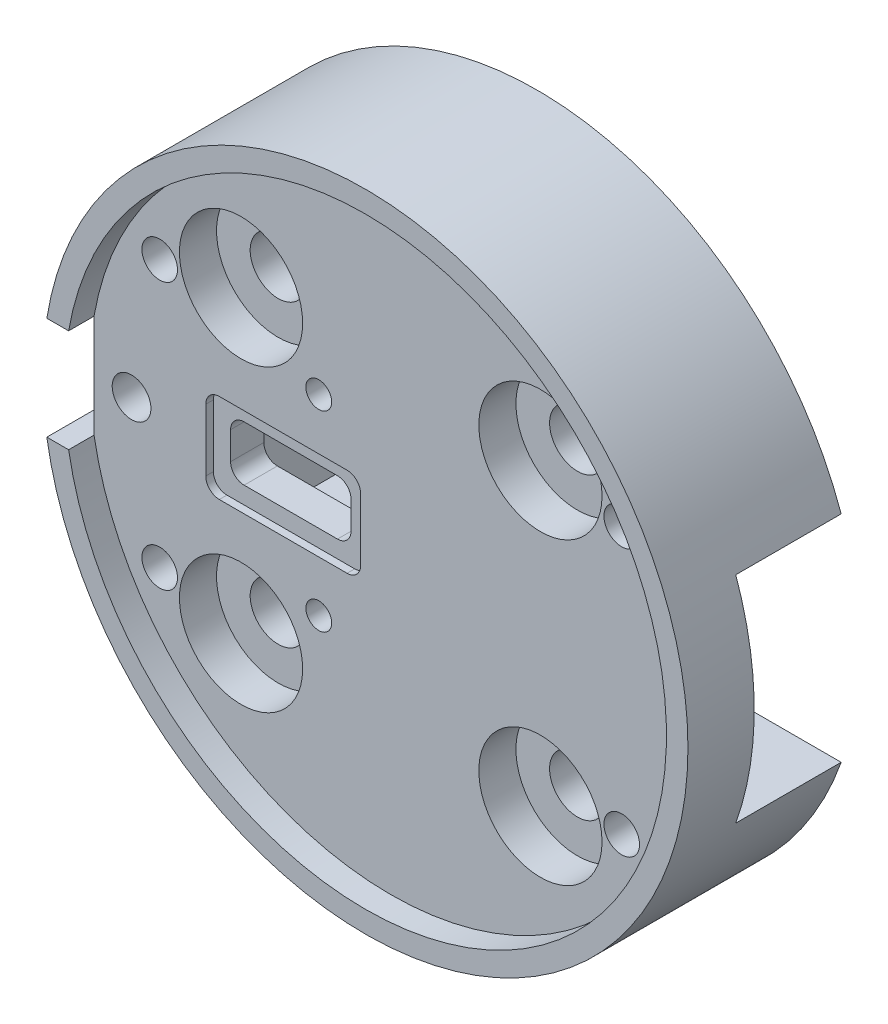
SolidWorks part; units mm, degrees
ref_plane "Front Plane" through (0, 0, 0) normal (0, 0, 1) x (1, 0, 0)
ref_plane "Top Plane" through (0, 0, 0) normal (0, 1, 0) x (1, 0, 0)
ref_plane "Right Plane" through (0, 0, 0) normal (1, 0, 0) x (0, 0, -1)
sketch "Sketch1" plane through (0, 0, 0) normal (0, 0, 1) x (1, 0, 0)
  circle A0 centre (0, 0) radius 38.1
  dimension "D1" = 76.2
extrude "Boss-Extrude1" add sketch "Sketch1" along normal blind 17.272 contours A0
sketch "Sketch2" plane through (0, 0, 17.272) normal (0, 0, 1) x (1, 0, 0)
  line L0 (0, 0) -> (38.1, 0) construction
  line L2 (0, 0) -> (17.6777, 17.6777) construction
  circle A0 centre (17.6777, 17.6777) radius 2.9
  circle A2 centre (17.6777, -17.6777) radius 2.9
  circle A3 centre (-17.6777, -17.6777) radius 2.9
  circle A5 centre (0, 0) radius 38.1 construction
  circle A6 centre (-17.6777, 17.6777) radius 2.9 [skipped]
  circle A7 centre (-17.6777, 17.6777) radius 2.9
  point P0 (17.6777, 17.6777)
  point P8 (17.6777, -17.6777)
  point P11 (-17.6777, -17.6777)
  point P39 (-17.6777, 17.6777)
  dimension "D1" = 5.8
  dimension "D4" = 5.8
  dimension "D3" = 45
  dimension "D5" = 25
  dimension "D6" = 25
  dimension "D2" = 4
hole_wizard "CBORE for M6 Hex Head Bolt1" positions "Sketch2" profile "Sketch5" counterbore size "M6" standard "ANSI Metric" end condition through all
sketch "Sketch5" plane through (17.6777, 17.6777, 17.272) normal (1, 0, 0) x (0, -1, 0)
  line L0 (0, 0) -> (0, 17.272)
  line L1 (0, 17.272) -> (3.3, 17.272)
  line L3 (3.3, 17.272) -> (3.3, 4.38)
  line L4 (3.3, 4.38) -> (7.275, 4.38)
  line L5 (7.275, 4.38) -> (7.275, 0)
  line L7 (7.275, 0) -> (0, 0)
  line L11 (0, -6.35) -> (0, 107.95) construction
  dimension "Thru Hole Dia." = 6.6
  dimension "Thru Hole Depth" = 17.272
  dimension "C'Bore Dia." = 14.55
  dimension "C'Bore Depth" = 4.38
sketch "Sketch6" plane through (0, 0, 17.272) normal (0, 0, 1) x (1, 0, 0)
  circle A1 centre (-5.653, 24.6769) radius 1.515
  dimension "D1" = 3.03
extrude "Pin_for_M6" cut sketch "Sketch6" against normal blind 17.272
sketch "Sketch7" plane through (0, 0, 17.272) normal (0, 0, 1) x (1, 0, 0)
  line L0 (0, 0) -> (0, 38.1) construction
  line L10 (0, 0) -> (27.2798, 15.75) construction
  line L12 (0, 0) -> (27.2798, -15.75) construction
  line L14 (-27.2798, 15.75) -> (0, 0) construction
  line L15 (0, 0) -> (-27.2798, -15.75) construction
  circle A0 centre (27.2798, 15.75) radius 2.4
  circle A1 centre (0, 0) radius 31.5 construction
  circle A2 centre (0, 0) radius 38.1 construction
  circle A4 centre (-27.2798, 15.75) radius 2.4
  circle A5 centre (27.2798, -15.75) radius 2.4
  circle A6 centre (-27.2798, -15.75) radius 2.4
  point P0 (27.2798, 15.75)
  point P5 (-27.2798, 15.75)
  point P17 (27.2798, -15.75)
  point P19 (-27.2798, -15.75)
  point P21 (-27.2798, 15.75)
  point P34 (-27.2798, -15.75)
  point P36 (27.2798, -15.75)
  point P38 (27.2798, 15.75)
  dimension "D2" = 4.8
  dimension "D1" = 4.8
  dimension "D3" = 63
  dimension "D4" = 60
  dimension "D5" = 60
  dimension "D6" = 120
hole_wizard "M5x0.8 Tapped Hole1" positions "Sketch7" profile "Sketch9" tap size "M5x0.8" standard "ANSI Metric" end condition through all
sketch "Sketch9" plane through (27.2798, 15.75, 17.272) normal (1, 0, 0) x (0, -1, 0)
  line L0 (0, 0) -> (0, 17.272)
  line L1 (0, 17.272) -> (2.1, 17.272)
  line L2 (2.1, 17.272) -> (2.1, 0)
  line L5 (2.1, 0) -> (0, 0)
  line L11 (0, -6.35) -> (0, 107.95) construction
  dimension "Thru Tap Drill Dia." = 4.2
  dimension "Thru Tap Drill Depth" = 17.272
cosmetic thread "Hole Thread1" parameters "D2"=5
cosmetic thread "Hole Thread2" parameters "D2"=5
cosmetic thread "Hole Thread3" parameters "D2"=5
cosmetic thread "Hole Thread4" parameters "D2"=5
cosmetic thread "Hole Thread5" parameters "D2"=5
cosmetic thread "Hole Thread6" parameters "D2"=5
cosmetic thread "Hole Thread7" parameters "D2"=5
cosmetic thread "Hole Thread8" parameters "D2"=5
sketch "Sketch10" plane through (0, 0, 17.272) normal (0, 0, 1) x (1, 0, 0)
  line L1 (-18.212, 3.2385) -> (-7.188, 3.2385)
  line L2 (-19.812, 1.6385) -> (-19.812, -1.6385)
  line L3 (-18.212, -3.2385) -> (-7.188, -3.2385)
  line L4 (-5.588, 1.6385) -> (-5.588, -1.6385)
  circle A0 centre (-5.653, 24.6769) radius 1.05
  arc A1 (-5.588, 1.6385) -> (-7.188, 3.2385) centre (-7.188, 1.6385) ccw
  arc A2 (-7.188, -3.2385) -> (-5.588, -1.6385) centre (-7.188, -1.6385) ccw
  arc A3 (-18.212, -3.2385) -> (-19.812, -1.6385) centre (-18.212, -1.6385) cw
  arc A4 (-19.812, 1.6385) -> (-18.212, 3.2385) centre (-18.212, 1.6385) cw
  point P4 (-19.812, 0)
  point P6 (-5.588, 0)
  point P13 (-5.588, 3.2385)
  point P18 (-19.812, -3.2385)
  point P21 (-19.812, 3.2385)
  dimension "D3" = 2.1
  dimension "D5" = 1.6
  dimension "D1" = 14.224
  dimension "D2" = 6.477
  dimension "D4" = 5.588
extrude "Spring_Pin_Hole" cut sketch "Sketch10" against normal blind 17.272
sketch "Sketch13" plane through (0, 0, 17.272) normal (0, 0, 1) x (1, 0, 0)
  line L2 (-37.6121, 6.078) -> (-35.0367, 6.078)
  line L4 (-37.6121, -6.078) -> (-35.0367, -6.078)
  arc A1 (-35.0367, 6.078) -> (35.0873, 5.7787) centre (0, 0) cw
  arc A3 (-35.0367, -6.078) -> (35.0873, 5.7787) centre (0, 0) ccw
  circle A5 centre (0, 0) radius 38.1 construction
  arc A7 (-37.6121, -6.078) -> (37.6592, -5.7785) centre (0, 0) ccw
  arc A16 (-37.6121, 6.078) -> (37.6592, -5.7785) centre (0, 0) cw
  dimension "D1" = 35.56
extrude "Allignment_Border" add sketch "Sketch13" along normal blind 3
sketch "Sketch15" plane through (0, 0, 17.272) normal (0, 0, 1) x (1, 0, 0)
  line L0 (-7.188, 3.2385) -> (-18.212, 3.2385) construction
  line L1 (-20.244, 5.2705) -> (-5.156, 5.2705)
  line L2 (-21.844, 3.6705) -> (-21.844, -3.6705)
  line L3 (-20.244, -5.2705) -> (-5.156, -5.2705)
  line L4 (-3.556, 3.6705) -> (-3.556, -3.6705)
  line L5 (-5.588, -1.6385) -> (-5.588, 1.6385) construction
  line L7 (-18.212, -3.2385) -> (-7.188, -3.2385) construction
  line L8 (-19.812, 1.6385) -> (-19.812, -1.6385) construction
  arc A0 (-21.844, -3.6705) -> (-20.244, -5.2705) centre (-20.244, -3.6705) ccw
  arc A1 (-21.844, 3.6705) -> (-20.244, 5.2705) centre (-20.244, 3.6705) cw
  arc A2 (-3.556, -3.6705) -> (-5.156, -5.2705) centre (-5.156, -3.6705) cw
  arc A3 (-3.556, 3.6705) -> (-5.156, 5.2705) centre (-5.156, 3.6705) ccw
  point P12 (-21.844, 5.2705)
  point P16 (-3.556, 5.2705)
  dimension "D2" = 2.032
  dimension "D1" = 2.032
extrude "Cut-Extrude2" cut sketch "Sketch15" against normal blind 0.9
sketch "Sketch16" plane through (0, 0, 17.272) normal (0, 0, 1) x (1, 0, 0)
  line L1 (-32.893, 0) -> (-28.321, 0) construction
  line L2 (-19.812, 1.6385) -> (-19.812, -1.6385) construction
  circle A0 centre (-30.607, 0) radius 2.286
  circle A1 centre (-24.5265, 0) radius 2.032 construction
  dimension "D1" = 8.509
  dimension "D3" = 4.064
  dimension "D4" = 4.572
  dimension "D2" = 13.081
extrude "R_Pin_Grounding" cut sketch "Sketch16" against normal blind 4.318
sketch "Sketch17" plane through (0, 0, 0) normal (0, 0, -1) x (-1, 0, 0)
  line L1 (-39.006, 12.7) -> (23.368, 12.7)
  line L2 (-39.006, 12.7) -> (-39.006, -12.7)
  line L3 (-39.006, -12.7) -> (23.368, -12.7)
  line L4 (23.368, 12.7) -> (23.368, -12.7)
  line L8 (0, 0) -> (26.67, 0) construction
  line L9 (-11.43, -19.9088) -> (11.43, -19.9088)
  line L10 (-11.43, -19.9088) -> (-11.43, 19.9678)
  line L11 (-11.43, 19.9678) -> (11.43, 19.9678)
  line L12 (11.43, -19.9088) -> (11.43, 19.9678)
  dimension "D1" = 12.7
  dimension "D3" = 11.43
  dimension "D4" = 11.43
extrude "Cut-Extrude3" cut sketch "Sketch17" against normal blind 12.446
sketch "Sketch18" plane through (0, 0, 17.272) normal (0, 0, 1) x (1, 0, 0)
  line L0 (-37.6121, 6.078) -> (-35.0367, 6.078) construction
  line L5 (-35.0367, 6.078) -> (-39.2748, 6.078)
  line L6 (-35.0367, 6.078) -> (-35.0367, -6.078)
  line L7 (-35.0367, -6.078) -> (-39.2748, -6.078)
  line L8 (-39.2748, 6.078) -> (-39.2748, -6.078)
extrude "Cut-Extrude4" cut sketch "Sketch18" against normal blind 5.08
sketch "Sketch19" plane through (0, 0, 0) normal (0, 0, -1) x (-1, 0, 0)
  circle A0 centre (5.653, 24.6769) radius 1.515
extrude "Boss-Extrude2" add sketch "Sketch19" against normal blind 17.272
sketch "Sketch20" plane through (0, 0, 12.446) normal (0, 0, -1) x (-1, 0, 0)
  line L0 (-11.43, 19.9678) -> (11.43, 19.9678) construction
  line L1 (-11.43, -19.9088) -> (11.43, -19.9088) construction
  circle A0 centre (8.4983, -11.2728) radius 1.524
  circle A1 centre (8.4983, 11.3318) radius 1.524
  point P4 (8.4983, 13.8718)
  dimension "D1" = 3.048
  dimension "D2" = 3.048
  dimension "D3" = 8.636
  dimension "D4" = 8.636
extrude "Cut-Extrude5" cut sketch "Sketch20" against normal blind 5.08
equation "\"compoent_thickness\"=0.68"
equation "\"D1@Boss-Extrude1\"=\"compoent_thickness\""
equation "\"D1@Pin_for_M6\"=\"compoent_thickness\""
equation "\"D1@Spring_Pin_Hole\" = \"compoent_thickness\""
equation "\"D1@Sketch7\"=\"D2@Sketch7\""
equation "\"D1@Cut-Extrude3\"=\"compoent_thickness\" - .19in"
equation "\"D1\"= 4.6mm"
equation "\"D5@Sketch15\"=\"D2@Sketch15\""
equation "\"D1@Sketch15\"=\"D2@Sketch15\""
equation "\"D6@Sketch15\"=\"D2@Sketch15\""
equation "\"D4@Sketch2\"=\"D1@Sketch2\""
equation "\"D2@Sketch17\"=\"D1@Sketch17\""
equation "\"D4@Sketch17\"=\"D3@Sketch17\""
equation "\"D1@Boss-Extrude2\"=\"compoent_thickness\""
equation "\"D2@Sketch20\"=\"D1@Sketch20\""
equation "\"D4@Sketch20\"=\"D3@Sketch20\""
